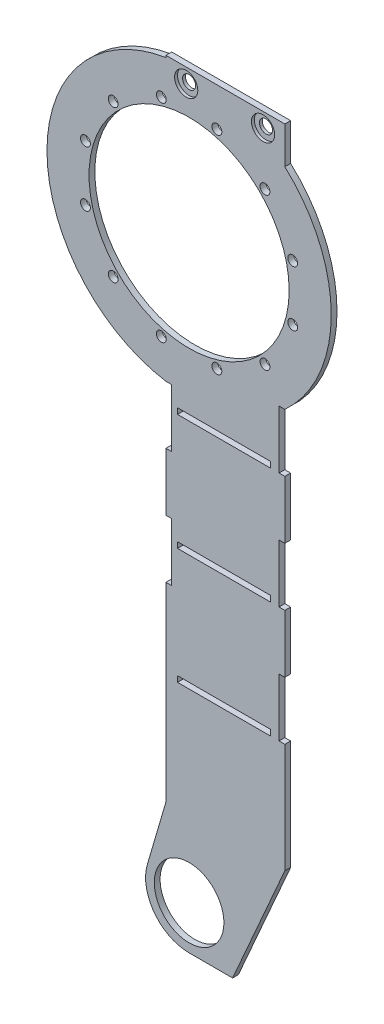
SolidWorks part; units mm, degrees
ref_plane "前视基准面" through (0, 0, 0) normal (0, 0, 1) x (1, 0, 0)
ref_plane "上视基准面" through (0, 0, 0) normal (0, 1, 0) x (1, 0, 0)
ref_plane "右视基准面" through (0, 0, 0) normal (1, 0, 0) x (0, 0, -1)
sketch "草图1" plane through (0, 0, 0) normal (0, 0, 1) x (1, 0, 0)
  line L93 (-8, -48.3425) -> (-6, -48.3425)
  line L100 (-6, -48.3425) -> (-6, -68.3425)
  line L101 (-6, -68.3425) -> (-8, -68.3425)
  line L102 (-8, -68.3425) -> (-8, -88.3425)
  line L103 (-8, -88.3425) -> (-6, -88.3425)
  line L104 (-6, -88.3425) -> (-6, -108.3425)
  line L105 (-6, -108.3425) -> (-8, -108.3425)
  line L106 (-8, -108.3425) -> (-8, -128.3425)
  line L108 (33, -36.2215) -> (31, -36.2215)
  line L109 (31, -36.2215) -> (31, -56.2215)
  line L110 (31, -56.2215) -> (33, -56.2215)
  line L111 (33, -56.2215) -> (33, -76.2215)
  line L112 (33, -76.2215) -> (31, -76.2215)
  line L113 (31, -76.2215) -> (31, -96.2215)
  line L114 (31, -96.2215) -> (33, -96.2215)
  line L117 (33, -96.2215) -> (33, -116.2215)
  line L118 (33, -116.2215) -> (31, -116.2215)
  line L119 (31, -116.2215) -> (31, -136.2215)
  line L120 (31, -136.2215) -> (33, -136.2215)
  line L121 (33, -136.2215) -> (33, -174)
  line L122 (-8, 49) -> (-8, 48.3425)
  line L124 (-8, 49) -> (33, 49)
  line L125 (33, 49) -> (33, 36.2215)
  line L128 (-4, -56.2215) -> (-4, -54.2215)
  line L129 (-4, -54.2215) -> (28, -54.2215)
  line L130 (28, -54.2215) -> (28, -56.2215)
  line L131 (-4, -56.2215) -> (28, -56.2215)
  line L134 (-4, -94.2215) -> (28, -94.2215)
  line L135 (-4, -96.2215) -> (28, -96.2215)
  line L136 (28, -94.2215) -> (28, -96.2215)
  line L137 (-4, -96.2215) -> (-4, -94.2215)
  line L138 (-4, -134.2215) -> (28, -134.2215)
  line L139 (-4, -136.2215) -> (28, -136.2215)
  line L140 (28, -134.2215) -> (28, -136.2215)
  line L141 (-4, -136.2215) -> (-4, -134.2215)
  line L145 (-8, -174) -> (-8, -128.3425)
  line L146 (-8, -174) -> (-14.3926, -195.7746)
  line L148 (0, -215) -> (15, -215)
  line L151 (15, -215) -> (33, -174)
  circle A13 centre (0, 0) radius 34.5
  arc A55 (-8, -48.3425) -> (-8, 48.3425) centre (0, 0) cw
  arc A56 (33, -36.2215) -> (33, 36.2215) centre (0, 0) ccw
  arc A61 (-14.3926, -195.7746) -> (0, -215) centre (0, -200) ccw
  circle A62 centre (0, -200) radius 12
  circle A64 centre (26.163, 26.163) radius 1.7
  circle A65 centre (35.7393, 9.5763) radius 1.7
  circle A66 centre (9.5763, 35.7393) radius 1.7
  circle A67 centre (-9.5763, 35.7393) radius 1.7
  circle A68 centre (-26.163, 26.163) radius 1.7
  circle A69 centre (-35.7393, 9.5763) radius 1.7
  circle A70 centre (-35.7393, -9.5763) radius 1.7
  circle A71 centre (-26.163, -26.163) radius 1.7
  circle A72 centre (-9.5763, -35.7393) radius 1.7
  circle A73 centre (9.5763, -35.7393) radius 1.7
  circle A74 centre (26.163, -26.163) radius 1.7
  circle A75 centre (35.7393, -9.5763) radius 1.7
  dimension "D1" = 3
extrude "凸台-拉伸1" add sketch "草图1" along normal blind 2
hole_wizard "M4 六角凹头盖的柱孔1" positions "3D草图1" profile "草图2" counterbore size "M4" standard "BSI" end condition through all
sketch3d "3D草图1"
  line L5 (-1, 44, 2) -> (25.5, 44, 2)
  point P19 (25.5, 44, 2)
  point P21 (-1, 44, 2)
  point P25 (-1, 44, 2)
sketch "草图2" plane through (-1, 44, 2) normal (1, 0, 0) x (0, -1, 0)
  line L0 (0, 0) -> (0, 2)
  line L1 (0, 2) -> (2.25, 2)
  line L3 (2.25, 2) -> (2.25, 1)
  line L4 (2.25, 1) -> (4, 1)
  line L5 (4, 1) -> (4, 0)
  line L7 (4, 0) -> (0, 0)
  line L11 (0, -6.35) -> (0, 107.95) construction
  dimension "通孔孔直径" = 4.5
  dimension "通孔孔深度" = 2
  dimension "柱形沉头孔直径" = 8
  dimension "柱形沉头孔深度" = 1
